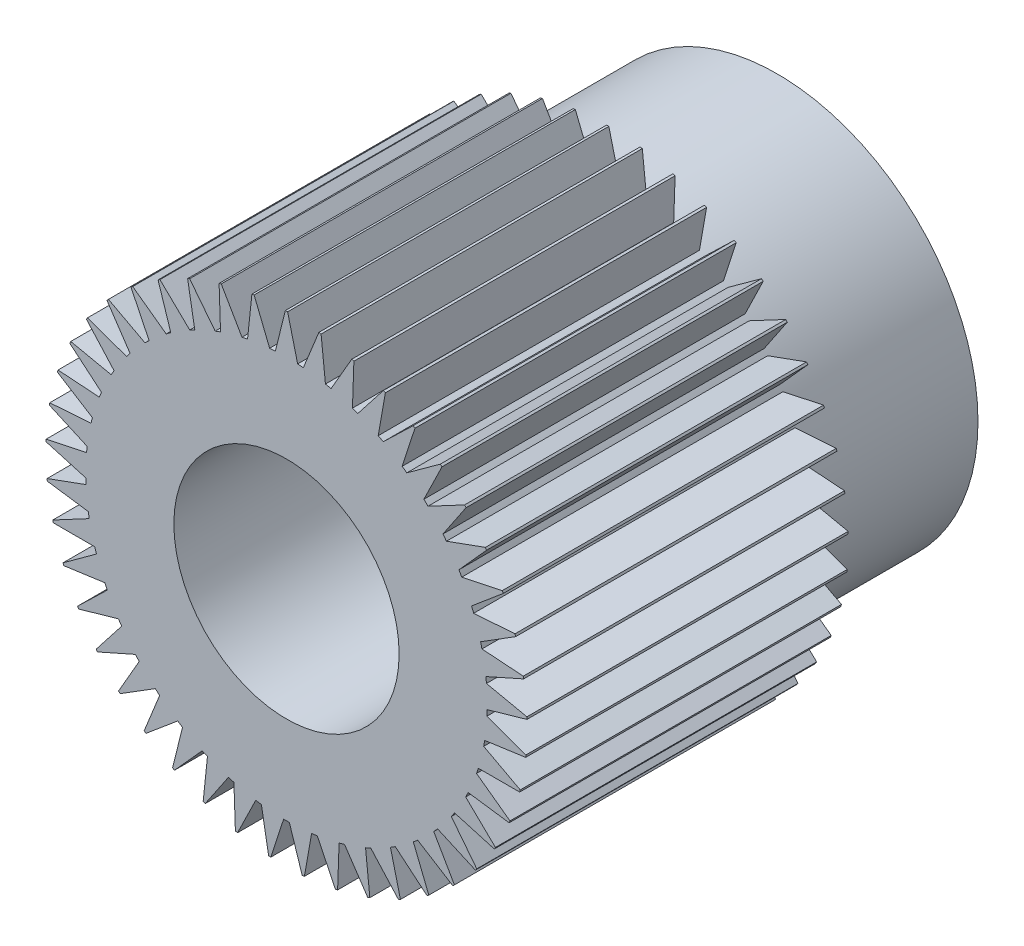
SolidWorks part; units mm, degrees
ref_plane "Front Plane" through (0, 0, 0) normal (0, 0, 1) x (1, 0, 0)
ref_plane "Top Plane" through (0, 0, 0) normal (0, 1, 0) x (1, 0, 0)
ref_plane "Right Plane" through (0, 0, 0) normal (1, 0, 0) x (0, 0, -1)
sketch "Sketch1" plane through (0, 0, 0) normal (0, 0, 1) x (1, 0, 0)
  circle A0 centre (0, 0) radius 4.5
  dimension "D1" = 9
extrude "Boss-Extrude1" add sketch "Sketch1" along normal blind 11
sketch "Sketch2" plane through (0, 0, 11) normal (0, 0, 1) x (1, 0, 0)
  circle A0 centre (0, 0) radius 2.525
  dimension "D1" = 5.05
extrude "Cut-Extrude1" cut sketch "Sketch2" against normal through all
sketch "Sketch3" plane through (0, 0, 11) normal (0, 0, 1) x (1, 0, 0)
  line L0 (-0.25, 4.4931) -> (-0.025, 5.3931)
  line L1 (0.025, 5.3931) -> (0.25, 4.4931)
  line L2 (0, 0) -> (0, 2.525) construction
  line L3 (-0.025, 5.3931) -> (0.025, 5.3931)
  circle A0 centre (0, 0) radius 4.5 construction
  circle A1 centre (0, 0) radius 2.525 construction
  arc A2 (-0.25, 4.4931) -> (0.25, 4.4931) centre (0, 0) cw
  point P1 (0, 0)
  dimension "D1" = 4.5
  dimension "D3" = 0.05
  dimension "D2" = 0.5
  dimension "D4" = 0.9
extrude "Boss-Extrude2" add sketch "Sketch3" against normal blind 7.2
pattern_circular "CirPattern2" count 45 every 8 about axis through (0, 0, 0) along (0, 0, 1) of "Boss-Extrude2"
